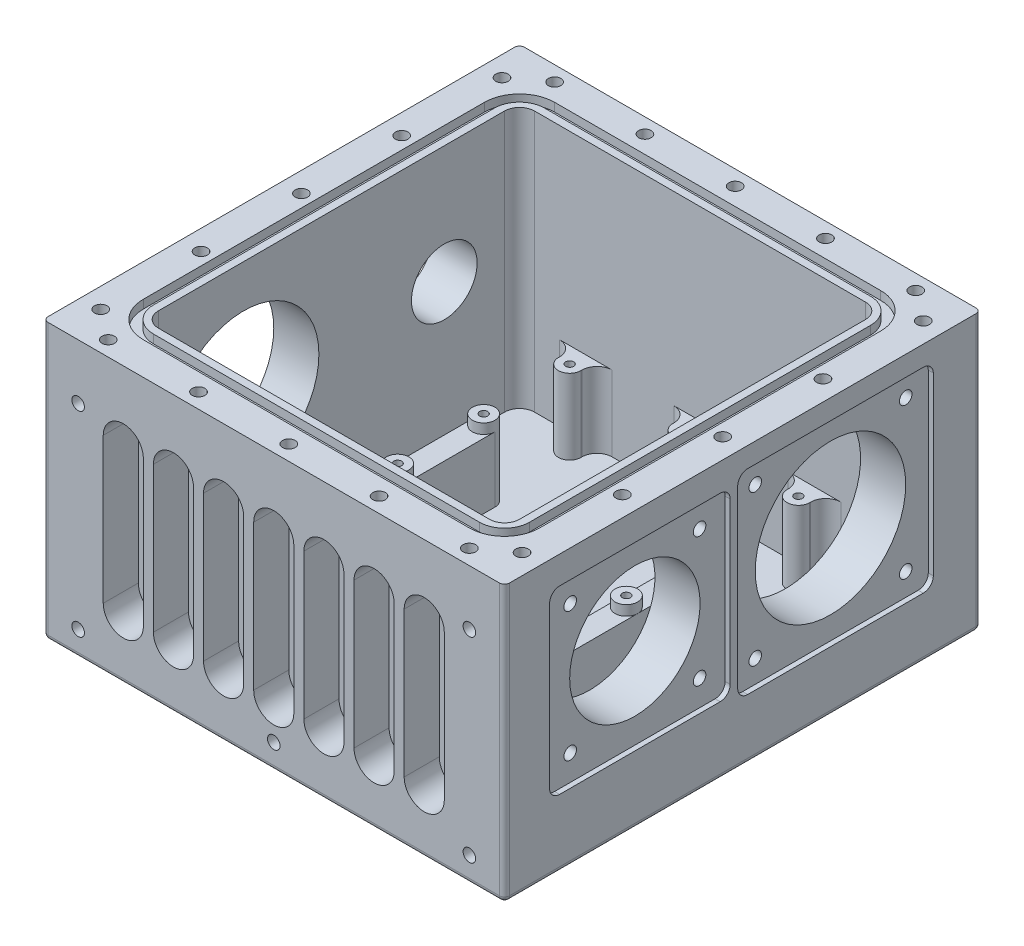
SolidWorks part; units mm, degrees
ref_plane "정면" through (0, 0, 0) normal (0, 0, 1) x (1, 0, 0)
ref_plane "윗면" through (0, 0, 0) normal (0, 1, 0) x (1, 0, 0)
ref_plane "우측면" through (0, 0, 0) normal (1, 0, 0) x (0, 0, -1)
ref_plane "평면1" through (0, 22.5, 0) normal (0, 1, 0) x (1, 0, 0)
sketch "스케치1" plane through (0, 22.5, 0) normal (0, 1, 0) x (1, 0, 0)
  line L0 (46, -95) -> (46, 0)
  line L1 (46, 0) -> (-46, 0)
  line L2 (-46, 0) -> (-46, -95)
  line L3 (-46, -95) -> (46, -95)
extrude "보스-돌출1" add sketch "스케치1" against normal blind 55
sketch "스케치2" plane through (0, 22.5, 0) normal (0, 1, 0) x (-1, 0, 0)
  line L0 (39.5, 6.5) -> (39.5, 88.5)
  line L1 (39.5, 88.5) -> (-39.5, 88.5)
  line L2 (-39.5, 88.5) -> (-39.5, 6.5)
  line L3 (-39.5, 6.5) -> (39.5, 6.5)
extrude "컷-돌출1" cut sketch "스케치2" against normal blind 1.7
sketch "스케치3" plane through (0, 20.8, 0) normal (0, 1, 0) x (-1, 0, 0)
  line L0 (37.5, 8.5) -> (-37.5, 8.5)
  line L1 (-37.5, 8.5) -> (-37.5, 86.5)
  line L2 (-37.5, 86.5) -> (37.5, 86.5)
  line L3 (37.5, 86.5) -> (37.5, 8.5)
extrude "보스-돌출2" add sketch "스케치3" along normal blind 1.7
sketch "스케치4" plane through (0, 22.5, 0) normal (0, 1, 0) x (-1, 0, 0)
  line L0 (36, 85) -> (-36, 85)
  line L1 (-36, 85) -> (-36, 10)
  line L2 (-36, 10) -> (36, 10)
  line L3 (36, 10) -> (36, 85)
extrude "컷-돌출2" cut sketch "스케치4" against normal blind 52
sketch "스케치5" plane through (0, -29.5, 0) normal (0, 1, 0) x (-1, 0, 0)
  line L0 (-20.55, 64.65) -> (-20.55, 30.35)
  line L1 (-25.05, 30.35) -> (-25.05, 64.65)
  arc A0 (-25.05, 64.65) -> (-20.55, 64.65) centre (-22.8, 64.65) cw
  arc A1 (-20.55, 30.35) -> (-25.05, 30.35) centre (-22.8, 30.35) cw
extrude "보스-돌출3" add sketch "스케치5" along normal blind 13
sketch "스케치6" plane through (0, -16.5, 0) normal (0, 1, 0) x (-1, 0, 0)
  circle A0 centre (-22.8, 30.35) radius 2.25
extrude "보스-돌출4" add sketch "스케치6" along normal blind 2
sketch "스케치7" plane through (0, -16.5, 0) normal (0, 1, 0) x (-1, 0, 0)
  circle A0 centre (-22.8, 64.65) radius 2.25
extrude "보스-돌출5" add sketch "스케치7" along normal blind 2
sketch "스케치8" plane through (0, -29.5, 0) normal (0, 1, 0) x (-1, 0, 0)
  line L0 (25.05, 64.65) -> (25.05, 30.35)
  line L1 (20.55, 30.35) -> (20.55, 64.65)
  arc A0 (20.55, 64.65) -> (25.05, 64.65) centre (22.8, 64.65) cw
  arc A1 (25.05, 30.35) -> (20.55, 30.35) centre (22.8, 30.35) cw
extrude "보스-돌출6" add sketch "스케치8" along normal blind 13
sketch "스케치9" plane through (0, -16.5, 0) normal (0, 1, 0) x (-1, 0, 0)
  circle A0 centre (22.8, 30.35) radius 2.25
extrude "보스-돌출7" add sketch "스케치9" along normal blind 2
sketch "스케치10" plane through (0, -16.5, 0) normal (0, 1, 0) x (-1, 0, 0)
  circle A0 centre (22.8, 64.65) radius 2.25
extrude "보스-돌출8" add sketch "스케치10" along normal blind 2
sketch "스케치11" plane through (0, -29.5, 0) normal (0, 1, 0) x (-1, 0, 0)
  line L0 (-20.55, 13.2) -> (-20.55, 10)
  line L1 (-20.55, 10) -> (-25.05, 10)
  line L2 (-25.05, 10) -> (-25.05, 13.2)
  arc A0 (-25.05, 13.2) -> (-20.55, 13.2) centre (-22.8, 13.2) cw
extrude "보스-돌출9" add sketch "스케치11" along normal blind 15
sketch "스케치12" plane through (0, -29.5, 0) normal (0, 1, 0) x (-1, 0, 0)
  line L0 (-25.05, 81.8) -> (-25.05, 85)
  line L1 (-25.05, 85) -> (-20.55, 85)
  line L2 (-20.55, 85) -> (-20.55, 81.8)
  arc A0 (-20.55, 81.8) -> (-25.05, 81.8) centre (-22.8, 81.8) cw
extrude "보스-돌출10" add sketch "스케치12" along normal blind 15
sketch "스케치13" plane through (0, -29.5, 0) normal (0, 1, 0) x (-1, 0, 0)
  line L0 (2.25, 13.2) -> (2.25, 10)
  line L1 (2.25, 10) -> (-2.25, 10)
  line L2 (-2.25, 10) -> (-2.25, 13.2)
  arc A0 (-2.25, 13.2) -> (2.25, 13.2) centre (0, 13.2) cw
extrude "보스-돌출11" add sketch "스케치13" along normal blind 15
sketch "스케치14" plane through (0, -29.5, 0) normal (0, 1, 0) x (-1, 0, 0)
  line L0 (25.05, 13.2) -> (25.05, 10)
  line L1 (25.05, 10) -> (20.55, 10)
  line L2 (20.55, 10) -> (20.55, 13.2)
  arc A0 (20.55, 13.2) -> (25.05, 13.2) centre (22.8, 13.2) cw
extrude "보스-돌출12" add sketch "스케치14" along normal blind 15
sketch "스케치15" plane through (0, -29.5, 0) normal (0, 1, 0) x (-1, 0, 0)
  line L0 (20.55, 81.8) -> (20.55, 85)
  line L1 (20.55, 85) -> (25.05, 85)
  line L2 (25.05, 85) -> (25.05, 81.8)
  arc A0 (25.05, 81.8) -> (20.55, 81.8) centre (22.8, 81.8) cw
extrude "보스-돌출13" add sketch "스케치15" along normal blind 15
sketch "스케치16" plane through (0, -29.5, 0) normal (0, 1, 0) x (-1, 0, 0)
  line L0 (-2.25, 81.8) -> (-2.25, 85)
  line L1 (-2.25, 85) -> (2.25, 85)
  line L2 (2.25, 85) -> (2.25, 81.8)
  arc A0 (2.25, 81.8) -> (-2.25, 81.8) centre (0, 81.8) cw
extrude "보스-돌출14" add sketch "스케치16" along normal blind 15
ref_plane "평면2" through (0, -14.5, 0) normal (0, 1, 0) x (1, 0, 0)
sketch "스케치17" plane through (0, -14.5, 0) normal (0, 1, 0) x (1, 0, 0)
  circle A0 centre (22.8, -47.5) radius 2.25
extrude "보스-돌출15" add sketch "스케치17" against normal up to next
sketch "스케치18" plane through (0, -14.5, 0) normal (0, 1, 0) x (1, 0, 0)
  circle A0 centre (-22.8, -47.5) radius 2.25
extrude "보스-돌출16" add sketch "스케치18" against normal up to next
sketch "스케치19" plane through (46, 0, 0) normal (1, 0, 0) x (0, 0, -1)
  line L0 (-48.5, -20.5) -> (-9.5, -20.5)
  line L1 (-9.5, -20.5) -> (-9.5, 18.5)
  line L2 (-9.5, 18.5) -> (-48.5, 18.5)
  line L3 (-48.5, 18.5) -> (-48.5, -20.5)
extrude "컷-돌출3" cut sketch "스케치19" against normal blind 1
sketch "스케치20" plane through (46, 0, 0) normal (1, 0, 0) x (0, 0, -1)
  line L0 (-86, 17) -> (-86, -19)
  line L1 (-86, -19) -> (-50, -19)
  line L2 (-50, -19) -> (-50, 17)
  line L3 (-50, 17) -> (-86, 17)
extrude "컷-돌출4" cut sketch "스케치20" against normal blind 1
sketch "스케치21" plane through (-46, 0, 0) normal (-1, 0, 0) x (0, 0, 1)
  line L0 (45.5, 18.5) -> (45.5, -20.5)
  line L1 (45.5, -20.5) -> (84.5, -20.5)
  line L2 (84.5, -20.5) -> (84.5, 18.5)
  line L3 (84.5, 18.5) -> (45.5, 18.5)
extrude "컷-돌출5" cut sketch "스케치21" against normal blind 1
sketch "스케치22" plane through (-46, 0, 0) normal (-1, 0, 0) x (0, 0, 1)
  line L0 (12, 12) -> (12, -14)
  line L1 (12, -14) -> (38, -14)
  line L2 (38, -14) -> (38, 12)
  line L3 (38, 12) -> (12, 12)
extrude "컷-돌출6" cut sketch "스케치22" against normal blind 1
sketch "스케치23" plane through (0, 0, 95) normal (0, 0, 1) x (1, 0, 0)
  line L0 (4, -20.5) -> (4, 8.5)
  line L1 (-4, 8.5) -> (-4, -20.5)
  arc A0 (4, 8.5) -> (-4, 8.5) centre (0, 8.5) ccw
  arc A1 (-4, -20.5) -> (4, -20.5) centre (0, -20.5) ccw
extrude "컷-돌출7" cut sketch "스케치23" against normal blind 7
sketch "스케치24" plane through (0, 0, 95) normal (0, 0, 1) x (1, 0, 0)
  line L0 (14, -20.5) -> (14, 8.5)
  line L1 (6, 8.5) -> (6, -20.5)
  arc A0 (14, 8.5) -> (6, 8.5) centre (10, 8.5) ccw
  arc A1 (6, -20.5) -> (14, -20.5) centre (10, -20.5) ccw
extrude "컷-돌출8" cut sketch "스케치24" against normal blind 7
sketch "스케치25" plane through (0, 0, 95) normal (0, 0, 1) x (1, 0, 0)
  line L0 (24, -20.5) -> (24, 8.5)
  line L1 (16, 8.5) -> (16, -20.5)
  arc A0 (24, 8.5) -> (16, 8.5) centre (20, 8.5) ccw
  arc A1 (16, -20.5) -> (24, -20.5) centre (20, -20.5) ccw
extrude "컷-돌출9" cut sketch "스케치25" against normal blind 7
sketch "스케치26" plane through (0, 0, 95) normal (0, 0, 1) x (1, 0, 0)
  line L0 (34, -20.5) -> (34, 8.5)
  line L1 (26, 8.5) -> (26, -20.5)
  arc A0 (34, 8.5) -> (26, 8.5) centre (30, 8.5) ccw
  arc A1 (26, -20.5) -> (34, -20.5) centre (30, -20.5) ccw
extrude "컷-돌출10" cut sketch "스케치26" against normal blind 7
sketch "스케치27" plane through (0, 0, 95) normal (0, 0, 1) x (1, 0, 0)
  line L0 (-6, -20.5) -> (-6, 8.5)
  line L1 (-14, 8.5) -> (-14, -20.5)
  arc A0 (-6, 8.5) -> (-14, 8.5) centre (-10, 8.5) ccw
  arc A1 (-14, -20.5) -> (-6, -20.5) centre (-10, -20.5) ccw
extrude "컷-돌출11" cut sketch "스케치27" against normal blind 7
sketch "스케치28" plane through (0, 0, 95) normal (0, 0, 1) x (1, 0, 0)
  line L0 (-16, -20.5) -> (-16, 8.5)
  line L1 (-24, 8.5) -> (-24, -20.5)
  arc A0 (-16, 8.5) -> (-24, 8.5) centre (-20, 8.5) ccw
  arc A1 (-24, -20.5) -> (-16, -20.5) centre (-20, -20.5) ccw
extrude "컷-돌출12" cut sketch "스케치28" against normal blind 7
sketch "스케치29" plane through (0, 0, 95) normal (0, 0, 1) x (1, 0, 0)
  line L0 (-26, -20.5) -> (-26, 8.5)
  line L1 (-34, 8.5) -> (-34, -20.5)
  arc A0 (-26, 8.5) -> (-34, 8.5) centre (-30, 8.5) ccw
  arc A1 (-34, -20.5) -> (-26, -20.5) centre (-30, -20.5) ccw
extrude "컷-돌출13" cut sketch "스케치29" against normal blind 7
sketch "스케치30" plane through (0, 0, 0) normal (0, 0, -1) x (-1, 0, 0)
  line L0 (-26, -20.5) -> (-26, 8.5)
  line L1 (-34, 8.5) -> (-34, -20.5)
  arc A0 (-26, 8.5) -> (-34, 8.5) centre (-30, 8.5) ccw
  arc A1 (-34, -20.5) -> (-26, -20.5) centre (-30, -20.5) ccw
extrude "컷-돌출14" cut sketch "스케치30" against normal blind 7
sketch "스케치31" plane through (0, 0, 0) normal (0, 0, -1) x (-1, 0, 0)
  line L0 (-16, -20.5) -> (-16, 8.5)
  line L1 (-24, 8.5) -> (-24, -20.5)
  arc A0 (-16, 8.5) -> (-24, 8.5) centre (-20, 8.5) ccw
  arc A1 (-24, -20.5) -> (-16, -20.5) centre (-20, -20.5) ccw
extrude "컷-돌출15" cut sketch "스케치31" against normal blind 7
sketch "스케치32" plane through (0, 0, 0) normal (0, 0, -1) x (-1, 0, 0)
  line L0 (-6, -20.5) -> (-6, 8.5)
  line L1 (-14, 8.5) -> (-14, -20.5)
  arc A0 (-6, 8.5) -> (-14, 8.5) centre (-10, 8.5) ccw
  arc A1 (-14, -20.5) -> (-6, -20.5) centre (-10, -20.5) ccw
extrude "컷-돌출16" cut sketch "스케치32" against normal blind 7
sketch "스케치33" plane through (0, 0, 0) normal (0, 0, -1) x (-1, 0, 0)
  line L0 (4, -20.5) -> (4, 8.5)
  line L1 (-4, 8.5) -> (-4, -20.5)
  arc A0 (4, 8.5) -> (-4, 8.5) centre (0, 8.5) ccw
  arc A1 (-4, -20.5) -> (4, -20.5) centre (0, -20.5) ccw
extrude "컷-돌출17" cut sketch "스케치33" against normal blind 7
sketch "스케치34" plane through (0, 0, 0) normal (0, 0, -1) x (-1, 0, 0)
  line L0 (14, -20.5) -> (14, 8.5)
  line L1 (6, 8.5) -> (6, -20.5)
  arc A0 (14, 8.5) -> (6, 8.5) centre (10, 8.5) ccw
  arc A1 (6, -20.5) -> (14, -20.5) centre (10, -20.5) ccw
extrude "컷-돌출18" cut sketch "스케치34" against normal blind 7
sketch "스케치35" plane through (0, 0, 0) normal (0, 0, -1) x (-1, 0, 0)
  line L0 (24, -20.5) -> (24, 8.5)
  line L1 (16, 8.5) -> (16, -20.5)
  arc A0 (24, 8.5) -> (16, 8.5) centre (20, 8.5) ccw
  arc A1 (16, -20.5) -> (24, -20.5) centre (20, -20.5) ccw
extrude "컷-돌출19" cut sketch "스케치35" against normal blind 7
sketch "스케치36" plane through (0, 0, 0) normal (0, 0, -1) x (-1, 0, 0)
  line L0 (34, -20.5) -> (34, 8.5)
  line L1 (26, 8.5) -> (26, -20.5)
  arc A0 (34, 8.5) -> (26, 8.5) centre (30, 8.5) ccw
  arc A1 (26, -20.5) -> (34, -20.5) centre (30, -20.5) ccw
extrude "컷-돌출20" cut sketch "스케치36" against normal blind 7
hole_wizard "M27 여유 구멍1" positions "스케치38" profile "스케치37" hole size "M27" standard "Ansi Metric"
sketch "스케치38" plane through (36, 0, 0) normal (-1, 0, 0) x (0, 0, 1)
  point P0 (29, -1)
sketch "스케치37" plane through (36, -1, 29) normal (0, 1, 0) x (0, 0, 1)
  line L0 (0, 0) -> (0, 10)
  line L1 (0, 10) -> (15, 10)
  line L2 (15, 10) -> (15, 0)
  line L5 (15, 0) -> (0, 0)
  line L11 (0, -6.35) -> (0, 107.95) construction
  dimension "관통 구멍 지름" = 30
  dimension "관통 구멍 깊이" = 10
hole_wizard "M22 여유 구멍1" positions "스케치40" profile "스케치39" hole size "M22" standard "Ansi Metric"
sketch "스케치40" plane through (36, 0, 0) normal (-1, 0, 0) x (0, 0, 1)
  point P0 (68, -1)
sketch "스케치39" plane through (36, -1, 68) normal (0, 1, 0) x (0, 0, 1)
  line L0 (0, 0) -> (0, 10)
  line L1 (0, 10) -> (13, 10)
  line L2 (13, 10) -> (13, 0)
  line L5 (13, 0) -> (0, 0)
  line L11 (0, -6.35) -> (0, 107.95) construction
  dimension "관통 구멍 지름" = 26
  dimension "관통 구멍 깊이" = 10
hole_wizard "Ø2.5 (2.5) 지름 구멍1" positions "스케치42" profile "스케치41" hole size "Ø2.5" standard "Ansi Metric"
sketch "스케치42" plane through (45, 0, 0) normal (1, 0, 0) x (0, 0, -1)
  point P0 (-55.1, 11.9)
  point P1 (-80.9, 11.9)
  point P2 (-80.9, -13.9)
  point P3 (-55.1, -13.9)
  point P4 (-44, 14)
  point P5 (-14, 14)
  point P6 (-44, -16)
  point P7 (-14, -16)
sketch "스케치41" plane through (45, 11.9, 55.1) normal (0, 1, 0) x (0, 0, -1)
  line L0 (0, 0) -> (0, 6.955)
  line L1 (0, 6.955) -> (1.25, 6.5)
  line L2 (1.25, 6.5) -> (1.25, 0)
  line L5 (1.25, 0) -> (0, 0)
  line L10 (0, 6.955) -> (-1.25, 6.5) construction
  line L11 (0, -6.35) -> (0, 107.95) construction
  dimension "구멍 지름" = 2.5
  dimension "구멍 깊이" = 6.5
  dimension "드릴 각도" = 140
hole_wizard "M27 여유 구멍2" positions "스케치44" profile "스케치43" hole size "M27" standard "Ansi Metric"
sketch "스케치44" plane through (-36, 0, 0) normal (1, 0, 0) x (0, 0, -1)
  point P0 (-65, -1)
sketch "스케치43" plane through (-36, -1, 65) normal (0, 1, 0) x (0, 0, -1)
  line L0 (0, 0) -> (0, 10)
  line L1 (0, 10) -> (15, 10)
  line L2 (15, 10) -> (15, 0)
  line L5 (15, 0) -> (0, 0)
  line L11 (0, -6.35) -> (0, 107.95) construction
  dimension "관통 구멍 지름" = 30
  dimension "관통 구멍 깊이" = 10
hole_wizard "M12 여유 구멍1" positions "스케치46" profile "스케치45" hole size "M12" standard "Ansi Metric"
sketch "스케치46" plane through (-36, 0, 0) normal (1, 0, 0) x (0, 0, -1)
  point P0 (-25, -1)
sketch "스케치45" plane through (-36, -1, 25) normal (0, 1, 0) x (0, 0, -1)
  line L0 (0, 0) -> (0, 10)
  line L1 (0, 10) -> (6.55, 10)
  line L2 (6.55, 10) -> (6.55, 0)
  line L5 (6.55, 0) -> (0, 0)
  line L11 (0, -6.35) -> (0, 107.95) construction
  dimension "관통 구멍 지름" = 13.1
  dimension "관통 구멍 깊이" = 10
hole_wizard "Ø2.5 (2.5) 지름 구멍2" positions "스케치48" profile "스케치47" hole size "Ø2.5" standard "Ansi Metric"
sketch "스케치48" plane through (-45, 0, 0) normal (-1, 0, 0) x (0, 0, 1)
  point P0 (33.35, 7.35)
  point P1 (16.65, 7.35)
  point P2 (16.65, -9.35)
  point P3 (33.35, -9.35)
  point P4 (50.9, 13.1)
  point P5 (50.9, -15.1)
  point P6 (79.1, -15.1)
  point P7 (79.1, 13.1)
sketch "스케치47" plane through (-45, 7.35, 33.35) normal (0, 1, 0) x (0, 0, 1)
  line L0 (0, 0) -> (0, 6.955)
  line L1 (0, 6.955) -> (1.25, 6.5)
  line L2 (1.25, 6.5) -> (1.25, 0)
  line L5 (1.25, 0) -> (0, 0)
  line L10 (0, 6.955) -> (-1.25, 6.5) construction
  line L11 (0, -6.35) -> (0, 107.95) construction
  dimension "구멍 지름" = 2.5
  dimension "구멍 깊이" = 6.5
  dimension "드릴 각도" = 140
hole_wizard "Ø2.5 (2.5) 지름 구멍3" positions "스케치50" profile "스케치49" hole size "Ø2.5" standard "Ansi Metric"
sketch "스케치50" plane through (0, 22.5, 0) normal (0, 1, 0) x (1, 0, 0)
  point P0 (-36, -3)
  point P1 (-18, -3)
  point P2 (0, -3)
  point P3 (18, -3)
  point P4 (36, -3)
  point P5 (-42, -7.5)
  point P6 (-42, -27.5)
  point P7 (-42, -47.5)
  point P8 (-42, -67.5)
  point P9 (-42, -87.5)
  point P10 (36, -92)
  point P11 (18, -92)
  point P12 (0, -92)
  point P13 (-18, -92)
  point P14 (-36, -92)
  point P15 (42, -87.5)
  point P16 (42, -67.5)
  point P17 (42, -47.5)
  point P18 (42, -27.5)
  point P19 (42, -7.5)
sketch "스케치49" plane through (-36, 22.5, 3) normal (1, 0, 0) x (0, 0, 1)
  line L0 (0, 0) -> (0, 7.955)
  line L1 (0, 7.955) -> (1.25, 7.5)
  line L2 (1.25, 7.5) -> (1.25, 0)
  line L5 (1.25, 0) -> (0, 0)
  line L10 (0, 7.955) -> (-1.25, 7.5) construction
  line L11 (0, -6.35) -> (0, 107.95) construction
  dimension "구멍 지름" = 2.5
  dimension "구멍 깊이" = 7.5
  dimension "드릴 각도" = 140
hole_wizard "Ø1.6 (1.6) 지름 구멍1" positions "스케치52" profile "스케치51" hole size "Ø1.6" standard "Ansi Metric"
sketch "스케치52" plane through (0, -14.5, 0) normal (0, 1, 0) x (1, 0, 0)
  point P0 (-22.8, -13.2)
  point P1 (0, -13.2)
  point P2 (22.8, -13.2)
  point P3 (-22.8, -30.35)
  point P4 (22.8, -30.35)
  point P5 (22.8, -47.5)
  point P6 (-22.8, -47.5)
  point P7 (-22.8, -64.65)
  point P8 (22.8, -64.65)
  point P9 (-22.8, -81.8)
  point P10 (0, -81.8)
  point P11 (22.8, -81.8)
sketch "스케치51" plane through (-22.8, -14.5, 13.2) normal (1, 0, 0) x (0, 0, 1)
  line L0 (0, 0) -> (0, 6.2912)
  line L1 (0, 6.2912) -> (0.8, 6)
  line L2 (0.8, 6) -> (0.8, 0)
  line L5 (0.8, 0) -> (0, 0)
  line L10 (0, 6.2912) -> (-0.8, 6) construction
  line L11 (0, -6.35) -> (0, 107.95) construction
  dimension "구멍 지름" = 1.6
  dimension "구멍 깊이" = 6
  dimension "드릴 각도" = 140
hole_wizard "Ø2.5 (2.5) 지름 구멍4" positions "스케치54" profile "스케치53" hole size "Ø2.5" standard "Ansi Metric"
sketch "스케치54" plane through (0, 0, 0) normal (0, 0, -1) x (-1, 0, 0)
  point P0 (-39, 11.5)
  point P1 (-39, -27.5)
  point P2 (39, -27.5)
  point P3 (39, 11.5)
  point P4 (0, -27.5)
sketch "스케치53" plane through (39, 11.5, 0) normal (1, 0, 0) x (0, 1, 0)
  line L0 (0, 0) -> (0, 8.955)
  line L1 (0, 8.955) -> (1.25, 8.5)
  line L2 (1.25, 8.5) -> (1.25, 0)
  line L5 (1.25, 0) -> (0, 0)
  line L10 (0, 8.955) -> (-1.25, 8.5) construction
  line L11 (0, -6.35) -> (0, 107.95) construction
  dimension "구멍 지름" = 2.5
  dimension "구멍 깊이" = 8.5
  dimension "드릴 각도" = 140
hole_wizard "Ø2.5 (2.5) 지름 구멍5" positions "스케치56" profile "스케치55" hole size "Ø2.5" standard "Ansi Metric"
sketch "스케치56" plane through (0, 0, 95) normal (0, 0, 1) x (1, 0, 0)
  point P0 (-39, 11.5)
  point P1 (39, 11.5)
  point P2 (39, -27.5)
  point P3 (0, -27.5)
  point P4 (-39, -27.5)
sketch "스케치55" plane through (-39, 11.5, 95) normal (1, 0, 0) x (0, -1, 0)
  line L0 (0, 0) -> (0, 8.955)
  line L1 (0, 8.955) -> (1.25, 8.5)
  line L2 (1.25, 8.5) -> (1.25, 0)
  line L5 (1.25, 0) -> (0, 0)
  line L10 (0, 8.955) -> (-1.25, 8.5) construction
  line L11 (0, -6.35) -> (0, 107.95) construction
  dimension "구멍 지름" = 2.5
  dimension "구멍 깊이" = 8.5
  dimension "드릴 각도" = 140
fillet "필렛1" radius 1 8 edges at (46, -5, 0) (0, -32.5, 0) (-46, -5, 0) (46, -5, 95) (46, -32.5, 47.5) (-46, -32.5, 47.5) (0, -32.5, 95) (-46, -5, 95)
fillet "필렛2" radius 2 16 edges at (-45.5, 18.5, 45.5) (-45.5, -14, 12) (45.5, -20.5, 9.5) (-45.5, -20.5, 84.5) (45.5, -19, 50) (45.5, 17, 50) (-45.5, -14, 38) (45.5, 17, 86) (45.5, 18.5, 9.5) (-45.5, 12, 12) (-45.5, 12, 38) (-45.5, -20.5, 45.5) (-45.5, 18.5, 84.5) (45.5, -20.5, 48.5) (45.5, 18.5, 48.5) (45.5, -19, 86)
fillet "필렛3" radius 3 16 edges at (2.25, -22, 85) (20.55, -22, 10) (-2.25, -22, 10) (-36, -3.5, 85) (25.05, -22, 85) (-36, -3.5, 10) (-20.55, -22, 10) (36, -3.5, 85) (2.25, -22, 10) (36, -3.5, 10) (25.05, -22, 10) (-2.25, -22, 85) (20.55, -22, 85) (-25.05, -22, 85) (-25.05, -22, 10) (-20.55, -22, 85)
fillet "필렛4" radius 5 4 edges at (-37.5, 21.65, 86.5) (37.5, 21.65, 8.5) (-37.5, 21.65, 8.5) (37.5, 21.65, 86.5)
fillet "필렛5" radius 7 4 edges at (39.5, 21.65, 88.5) (-39.5, 21.65, 88.5) (39.5, 21.65, 6.5) (-39.5, 21.65, 6.5)
